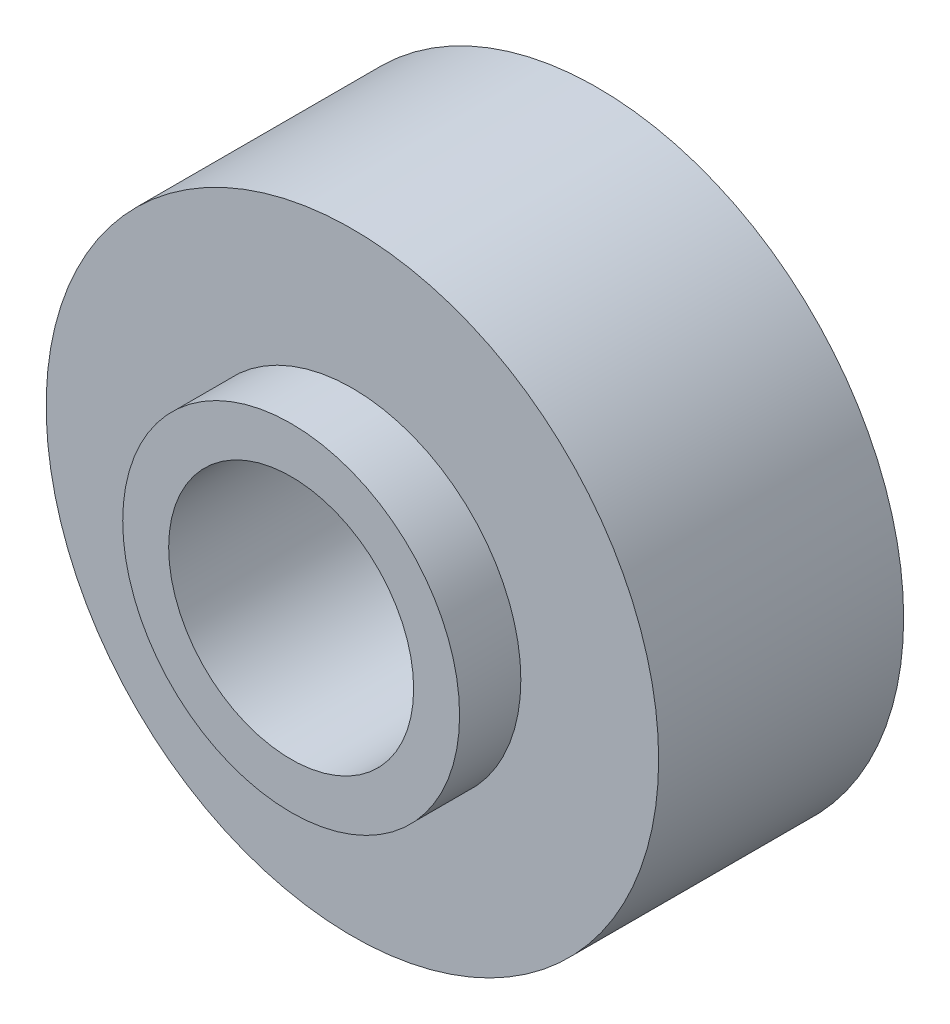
SolidWorks part; units mm, degrees
ref_plane "Спереди" through (0, 0, 0) normal (0, 0, 1) x (1, 0, 0)
ref_plane "Сверху" through (0, 0, 0) normal (0, 1, 0) x (1, 0, 0)
ref_plane "Справа" through (0, 0, 0) normal (1, 0, 0) x (0, 0, -1)
sketch "Эскиз1" plane through (0, 0, 0) normal (0, 0, 1) x (1, 0, 0)
  circle A0 centre (0, 0) radius 10
  circle A1 centre (0, 0) radius 4
  dimension "D1" = 8
  dimension "D2" = 20
extrude "Бобышка-Вытянуть1" add sketch "Эскиз1" against normal blind 10
sketch "Эскиз2" plane through (0, 0, 0) normal (0, 0, 1) x (1, 0, 0)
  circle A0 centre (0, 0) radius 10
  circle A1 centre (0, 0) radius 5.5
  dimension "D1" = 11
extrude "Вырез-Вытянуть1" cut sketch "Эскиз2" against normal blind 2
